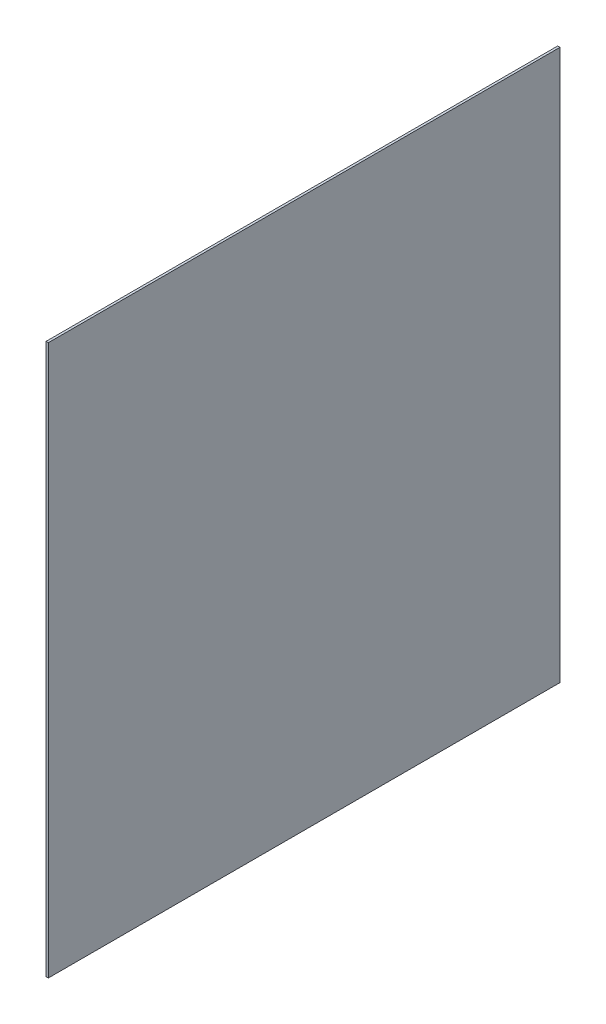
SolidWorks part; units mm, degrees
ref_plane "Front Plane" through (0, 0, 0) normal (0, 0, 1) x (1, 0, 0)
ref_plane "Top Plane" through (0, 0, 0) normal (0, 1, 0) x (1, 0, 0)
ref_plane "Right Plane" through (0, 0, 0) normal (1, 0, 0) x (0, 0, -1)
sketch "Sketch1" plane through (0, 0, 0) normal (0, 1, 0) x (1, 0, 0)
  line L1 (1.5875, 353.06) -> (-1.5875, 353.06)
  line L2 (1.5875, 353.06) -> (1.5875, -353.06)
  line L3 (1.5875, -353.06) -> (-1.5875, -353.06)
  line L4 (-1.5875, 353.06) -> (-1.5875, -353.06)
  line L5 (1.5875, 353.06) -> (-1.5875, -353.06) construction
  line L6 (1.5875, -353.06) -> (-1.5875, 353.06) construction
  point P0 (0, 0)
  dimension "D1" = 3.175
  dimension "D2" = 706.12
extrude "Boss-Extrude1" add sketch "Sketch1" along normal blind 759.46 contours L2 L3 L4 L1
